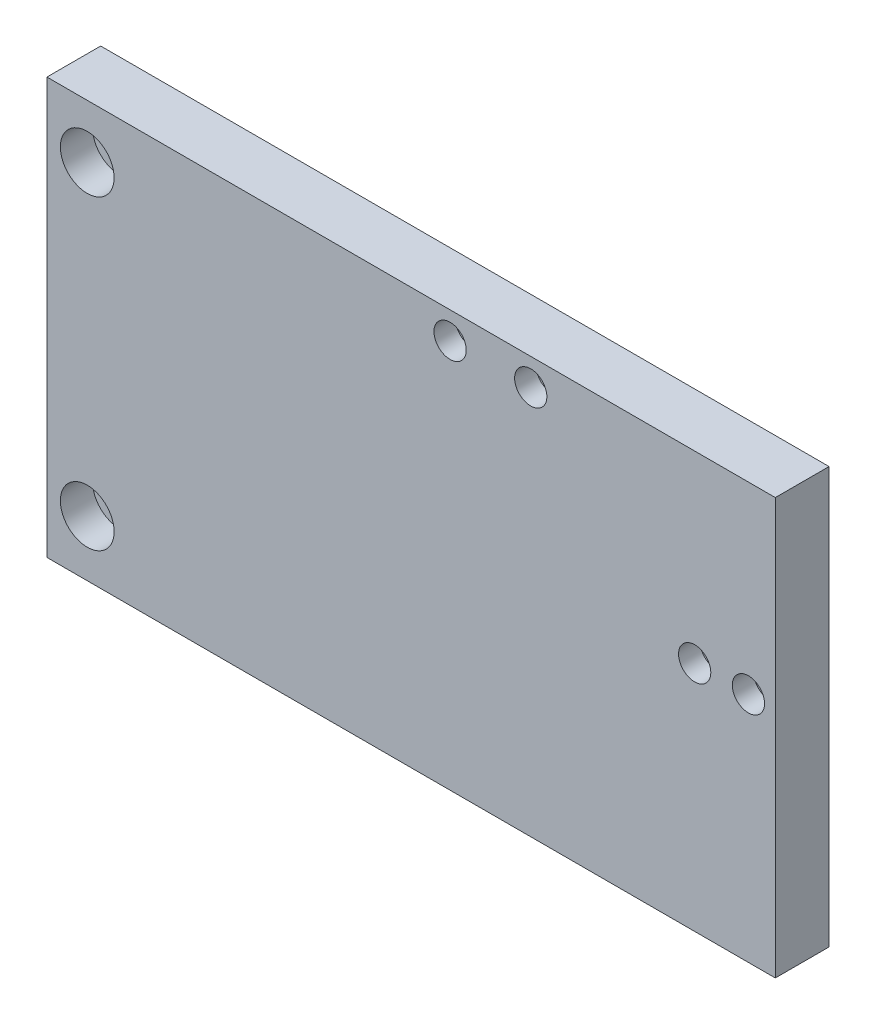
SolidWorks part; units mm, degrees
material "2024-T3"
ref_plane "正面" through (0, 0, 0) normal (0, 0, 1) x (1, 0, 0)
ref_plane "平面" through (0, 0, 0) normal (0, 1, 0) x (1, 0, 0)
ref_plane "右側面" through (0, 0, 0) normal (1, 0, 0) x (0, 0, -1)
sketch "ｽｹｯﾁ1" plane through (0, 0, 0) normal (0, 0, 1) x (1, 0, 0)
  line L1 (0, 0) -> (135.5, 0)
  line L2 (0, 0) -> (0, 77.4)
  line L3 (0, 77.4) -> (135.5, 77.4)
  line L4 (135.5, 0) -> (135.5, 77.4)
  dimension "D1" = 77.4
  dimension "D2" = 135.5
extrude "ﾎﾞｽ - 押し出し1" add sketch "ｽｹｯﾁ1" along normal blind 10
sketch "ｽｹｯﾁ3" plane through (0, 0, 10) normal (0, 0, 1) x (1, 0, 0)
  line L0 (0, 77.4) -> (0, 0) construction
  line L1 (70, 77.4) -> (95, 77.4)
  line L2 (70, 77.4) -> (70, 67.4)
  line L3 (70, 67.4) -> (95, 67.4)
  line L4 (95, 77.4) -> (95, 67.4)
  line L6 (115.5, 48.2) -> (115.5, 38.2)
  line L7 (115.5, 38.2) -> (135.5, 38.2)
  line L8 (135.5, 48.2) -> (135.5, 38.2)
  line L10 (115.5, 48.2) -> (135.5, 48.2)
  line L11 (0, 0) -> (135.5, 0) construction
  line L13 (135.5, 0) -> (135.5, 77.4) construction
  line L14 (135.5, 77.4) -> (0, 77.4) construction
  line L15 (70, 72.4) -> (95, 72.4)
  line L16 (115.5, 43.2) -> (135.5, 43.2)
  point P24 (75, 72.4)
  point P25 (90, 72.4)
  point P26 (120.5, 43.2)
  point P27 (130.5, 43.2)
  dimension "D1" = 10
  dimension "D2" = 25
  dimension "D3" = 70
  dimension "D4" = 10
  dimension "D5" = 20
  dimension "D6" = 38.2
  dimension "D7" = 5
  dimension "D8" = 5
  dimension "D9" = 5
  dimension "D10" = 5
sketch "ｽｹｯﾁ4" plane through (0, 0, 10) normal (0, 0, 1) x (1, 0, 0)
  point P0 (130.5, 43.2)
  point P2 (120.5, 43.2)
hole_wizard "M3 穴付きねじ用座ぐり穴1" positions "ｽｹｯﾁ4" profile "ｽｹｯﾁ5" counterbore size "M3" standard "JIS" end condition up to next
sketch "ｽｹｯﾁ5" plane through (130.5, 43.2, 10) normal (1, 0, 0) x (0, -1, 0)
  line L0 (0, 0) -> (0, 10)
  line L1 (0, 10) -> (1.7, 10)
  line L3 (1.7, 10) -> (1.7, 4)
  line L4 (1.7, 4) -> (3, 4)
  line L5 (3, 4) -> (3, 0)
  line L7 (3, 0) -> (0, 0)
  line L11 (0, -6.35) -> (0, 107.95) construction
  dimension "通し穴の直径" = 3.4
  dimension "通し穴の深さ" = 10
  dimension "座ぐり穴の直径" = 6
  dimension "座ぐり穴の深さ" = 4
hole_wizard "M3 穴付きねじ用座ぐり穴2" positions "ｽｹｯﾁ3" profile "ｽｹｯﾁ6" counterbore size "M3" standard "JIS" end condition through all
sketch "ｽｹｯﾁ6" plane through (130.5, 43.2, 10) normal (1, 0, 0) x (0, -1, 0)
  line L0 (0, 0) -> (0, 10)
  line L1 (0, 10) -> (1.7, 10)
  line L3 (1.7, 10) -> (1.7, 4)
  line L4 (1.7, 4) -> (3, 4)
  line L5 (3, 4) -> (3, 0)
  line L7 (3, 0) -> (0, 0)
  line L11 (0, -6.35) -> (0, 107.95) construction
  dimension "通し穴の直径" = 3.4
  dimension "通し穴の深さ" = 10
  dimension "座ぐり穴の直径" = 6
  dimension "座ぐり穴の深さ" = 4
sketch "ｽｹｯﾁ7" plane through (0, 0, 10) normal (0, 0, 1) x (1, 0, 0)
  line L0 (135.5, 77.4) -> (0, 77.4) construction
  line L1 (0, 77.4) -> (0, 0) construction
  point P0 (7.5, 67.4)
  point P1 (7.5, 10.4)
  dimension "D1" = 10
  dimension "D2" = 7.5
  dimension "D3" = 57
  dimension "D4" = 7.5
hole_wizard "M5 穴付きねじ用座ぐり穴1" positions "ｽｹｯﾁ7" profile "ｽｹｯﾁ8" counterbore size "M5" standard "JIS" end condition through all
sketch "ｽｹｯﾁ8" plane through (7.5, 67.4, 10) normal (1, 0, 0) x (0, -1, 0)
  line L0 (0, 0) -> (0, 10)
  line L1 (0, 10) -> (2.75, 10)
  line L3 (2.75, 10) -> (2.75, 6)
  line L4 (2.75, 6) -> (5, 6)
  line L5 (5, 6) -> (5, 0)
  line L7 (5, 0) -> (0, 0)
  line L11 (0, -6.35) -> (0, 107.95) construction
  dimension "通し穴の直径" = 5.5
  dimension "通し穴の深さ" = 10
  dimension "座ぐり穴の直径" = 10
  dimension "座ぐり穴の深さ" = 6
